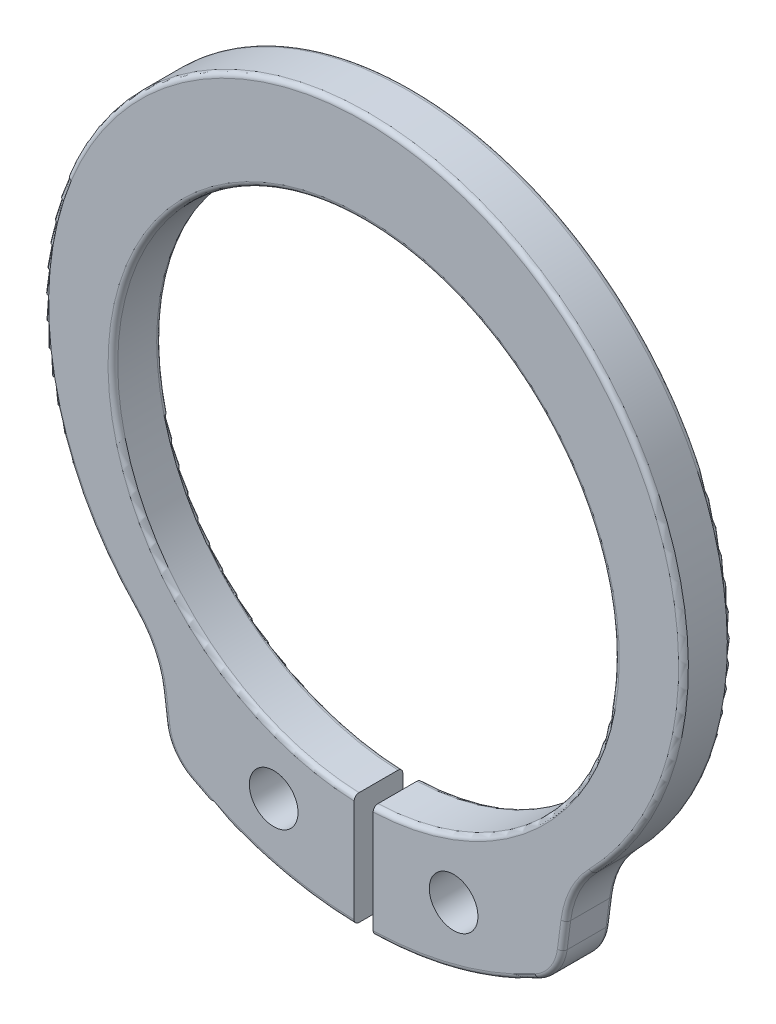
SolidWorks part; units mm, degrees
ref_plane "Front" through (0, 0, 0) normal (0, 0, 1) x (1, 0, 0)
ref_plane "Top" through (0, 0, 0) normal (0, 1, 0) x (1, 0, 0)
ref_plane "Right" through (0, 0, 0) normal (1, 0, 0) x (0, 0, -1)
sketch "Sketch1" plane through (0, 0, 0) normal (0, 0, 1) x (1, 0, 0)
  line L1 (0, 14.7828) -> (0, -14.7828) construction
  line L2 (-7.9639, -12.4602) -> (-8.4146, -8.9973) construction
  line L4 (-8.4146, -8.9973) -> (-9.5423, -10.2032) construction
  line L5 (-8.4146, -8.9973) -> (0, 0) construction
  line L6 (0, 10.2108) -> (0, 13.97) construction
  line L7 (0, 13.97) -> (0, 12.0904) construction
  line L8 (0, -10.2108) -> (0, -14.7828) construction
  line L9 (-4.334, -14.1385) -> (0, 0) construction
  line L10 (0, 0) -> (-0.3871, -14.7828) construction
  line L11 (-7.9639, -12.4602) -> (0, 0) construction
  line L14 (-2.9926, -9.7624) -> (-4.334, -14.1385) construction
  line L15 (-3.6633, -11.9505) -> (-2.7162, -12.2408) construction
  arc A0 (0, 13.97) -> (-8.4146, -8.9973) centre (0, 0.9449) ccw construction
  circle A2 centre (0, 0) radius 13.97 construction
  arc A3 (-7.9639, -12.4602) -> (-0.3871, -14.7828) centre (0, 0) ccw construction
  circle A4 centre (0, 0) radius 10.2108 construction
  circle A6 centre (-3.6633, -11.9505) radius 0.9906 construction
  point P1 (-6.9746, -7.4576)
  dimension "Ring ID" = 20.4216
  dimension "Hole Diameter" = 1.9812
  dimension "Max Sec." = 3.7592
  dimension "Lug Height" = 4.572
  dimension "D6" = 1.5
  dimension "Min Sec." = 2.1082
  dimension "D1" = 7.9248
  dimension "D2" = 40
sketch "Sketch2" plane through (0, 0, 0) normal (0, 1, 0) x (1, 0, 0)
  line L0 (-12.9908, 0.9906) -> (-12.9908, -0.9906) construction
  point P3 (-12.9908, 0)
  dimension "Ring Thickness" = 1.9812
sketch "Sketch3" plane through (0, 0, 0) normal (0, 0, 1) x (1, 0, 0)
  line L0 (-7.9639, -12.4602) -> (-8.4146, -8.9973) construction
  line L1 (-7.9639, -12.4602) -> (-8.4146, -8.9973)
  line L2 (0, 13.97) -> (0, 10.2108)
  line L3 (-0.3871, -14.7828) -> (-0.3871, -10.2035)
  arc A0 (0, 13.97) -> (-8.4146, -8.9973) centre (0, 0.9449) ccw construction
  arc A1 (-7.9639, -12.4602) -> (-0.3871, -14.7828) centre (0, 0) ccw construction
  circle A2 centre (-3.6633, -11.9505) radius 0.9906 construction
  arc A4 (0, 13.97) -> (-8.4146, -8.9973) centre (0, 0.9449) ccw
  arc A5 (-7.9639, -12.4602) -> (-0.3871, -14.7828) centre (0, 0) ccw
  circle A6 centre (-3.6633, -11.9505) radius 0.9906
  circle A7 centre (0, 0) radius 10.2108 construction
  arc A8 (0, 10.2108) -> (-0.3871, -10.2035) centre (0, 0) ccw
extrude "Boss-Extrude1" add sketch "Sketch3" along normal mid plane 1.9812
fillet "Fillet1" radius 3.9624 1 edges at (-8.4146, -8.9973, 0)
fillet "Fillet2" radius 1.9812 1 edges at (-7.9639, -12.4602, 0)
mirror "Mirror1" about plane through (0, 13.97, 0.9906) normal (-1, 0, 0) of bodies 109
fillet "Fillet3" radius 0.1981 20 edges at (-3.8356, -14.2818, -0.9906) (-7.7581, -12.3677, -0.9906) (-8.1599, -10.9543, -0.9906) (-8.5948, -9.1888, -0.9906) (0, 13.97, -0.9906) (8.5948, -9.1888, 0.9906) (8.5948, -9.1888, -0.9906) (3.8356, -14.2818, 0.9906) (3.8356, -14.2818, -0.9906) (7.7581, -12.3677, 0.9906) (7.7581, -12.3677, -0.9906) (8.1599, -10.9543, -0.9906) (8.1599, -10.9543, 0.9906) (0, 13.97, 0.9906) (-8.5948, -9.1888, 0.9906) (-3.8356, -14.2818, 0.9906) (-7.7581, -12.3677, 0.9906) (0, 10.2108, -0.9906) (-8.1599, -10.9543, 0.9906) (0, 10.2108, 0.9906)
sketch "Sketch4" plane through (0, 0, 0) normal (0, 0, 1) x (1, 0, 0)
  line L1 (-8.8428, -5.1054) -> (0, 0) construction
  line L2 (0, 14.7828) -> (0, -14.7828) construction
  circle A0 centre (0, 0) radius 10.2108 construction
  point P0 (-8.8428, -5.1054)
  dimension "D1" = 60
equation "\"D1@Boss-Extrude1\" = \"Ring Thickness@Sketch2\""
equation "\"D1@Sketch1\"=\"Hole Diameter@Sketch1\"*4"
equation "\"D1@Fillet1\"=\"Hole Diameter@Sketch1\"*2"
equation "\"D1@Fillet2\"=\"D1@Fillet1\"*.5"
equation "\"D1@Fillet3\"=\"Hole Diameter@Sketch1\"*.1"
